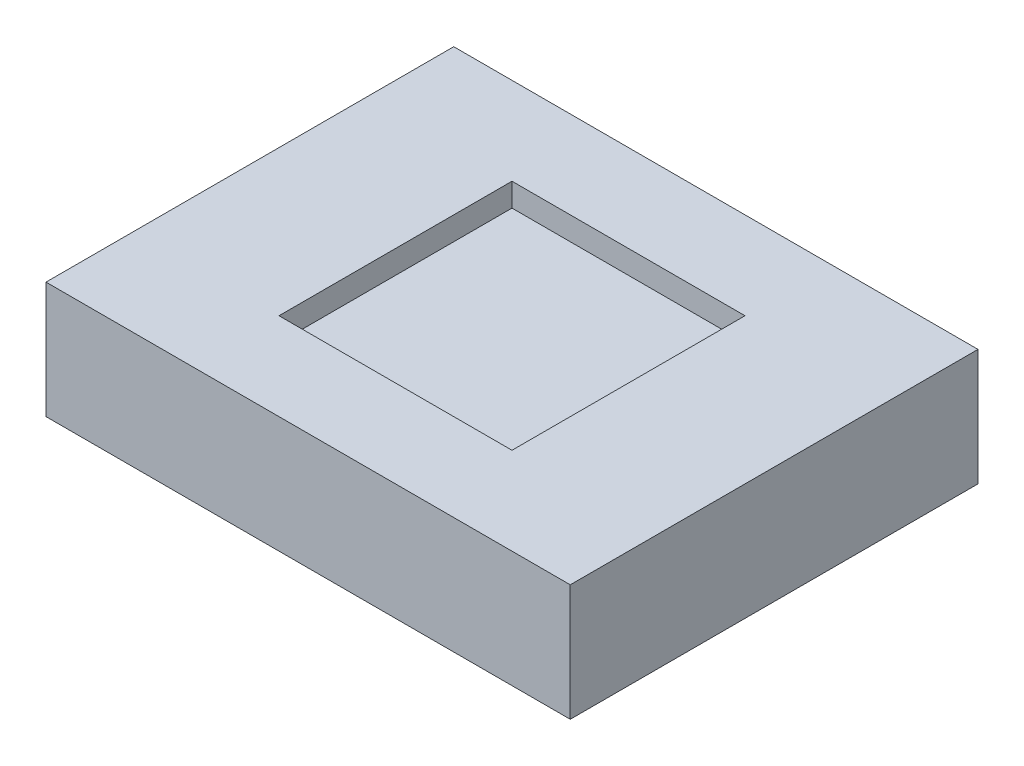
SolidWorks part; units mm, degrees
material "PET"
ref_plane "Front Plane" through (0, 0, 0) normal (0, 0, 1) x (1, 0, 0)
ref_plane "Top Plane" through (0, 0, 0) normal (0, 1, 0) x (1, 0, 0)
ref_plane "Right Plane" through (0, 0, 0) normal (1, 0, 0) x (0, 0, -1)
sketch "Sketch2" plane through (0, 0, 0) normal (0, 1, 0) x (1, 0, 0)
  line L1 (-22.5, 17.5) -> (22.5, 17.5)
  line L2 (-22.5, 17.5) -> (-22.5, -17.5)
  line L3 (-22.5, -17.5) -> (22.5, -17.5)
  line L4 (22.5, 17.5) -> (22.5, -17.5)
  line L5 (-22.5, 17.5) -> (22.5, -17.5) construction
  line L6 (-22.5, -17.5) -> (22.5, 17.5) construction
  point P0 (0, 0)
  dimension "D1" = 45
  dimension "D2" = 35
extrude "Boss-Extrude1" add sketch "Sketch2" along normal blind 10
sketch "Sketch3" plane through (0, 10, 0) normal (0, 1, 0) x (1, 0, 0)
  line L1 (-10, 10) -> (10, 10)
  line L2 (-10, 10) -> (-10, -10)
  line L3 (-10, -10) -> (10, -10)
  line L4 (10, 10) -> (10, -10)
  line L5 (-10, 10) -> (10, -10) construction
  line L6 (-10, -10) -> (10, 10) construction
  point P0 (0, 0)
  dimension "D1" = 20
  dimension "D2" = 20
extrude "Cut-Extrude1" cut sketch "Sketch3" against normal blind 2 contours L2 L1 L4 L3
sketch "Sketch10" plane through (0, 0, 0) normal (0, -1, 0) x (1, 0, 0)
  line L1 (-18.75, 13.75) -> (18.75, 13.75)
  line L2 (-18.75, 13.75) -> (-18.75, -13.75)
  line L3 (-18.75, -13.75) -> (18.75, -13.75)
  line L4 (18.75, 13.75) -> (18.75, -13.75)
  line L5 (-18.75, 13.75) -> (18.75, -13.75) construction
  line L6 (-18.75, -13.75) -> (18.75, 13.75) construction
  circle A0 centre (-18.75, 13.75) radius 2.85
  circle A1 centre (18.7544, 13.75) radius 2.85
  circle A2 centre (18.7544, -13.75) radius 2.85
  circle A3 centre (-18.75, -13.75) radius 2.85
  point P0 (0, 0)
  dimension "D3" = 5.7
  dimension "D1" = 27.5
  dimension "D2" = 37.5
  dimension "D4" = 2
  dimension "D5" = 2
extrude "Cut-Extrude2" cut sketch "Sketch10" against normal blind 7 contours A0 | A1 | A3 | A2
